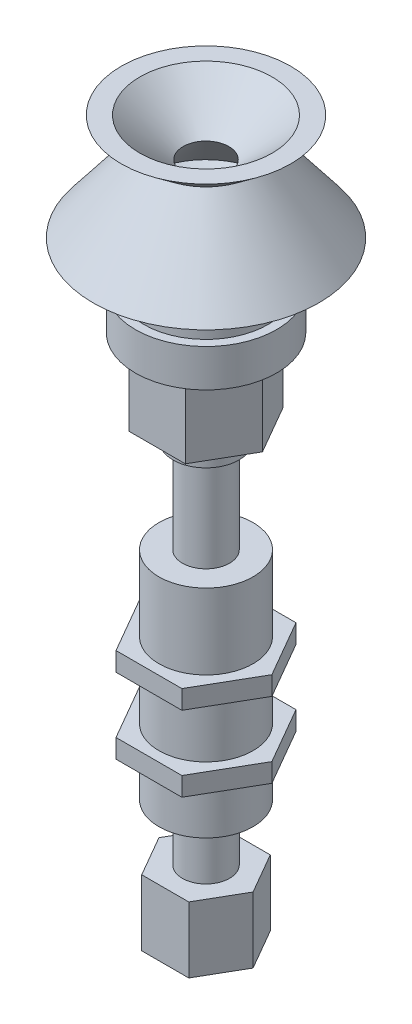
SolidWorks part; units mm, degrees
ref_plane "前视基准面" through (0, 0, 0) normal (0, 0, 1) x (1, 0, 0)
ref_plane "上视基准面" through (0, 0, 0) normal (0, 1, 0) x (1, 0, 0)
ref_plane "右视基准面" through (0, 0, 0) normal (1, 0, 0) x (0, 0, -1)
other "Configuration Table"
sketch "草图1" plane through (0, 0, 0) normal (0, 1, 0) x (1, 0, 0)
  line L1 (-2.5, -4.3301) -> (2.5, -4.3301)
  line L2 (2.5, -4.3301) -> (5, 0)
  line L3 (5, 0) -> (2.5, 4.3301)
  line L4 (2.5, 4.3301) -> (-2.5, 4.3301)
  line L5 (-2.5, 4.3301) -> (-5, 0)
  line L6 (-5, 0) -> (-2.5, -4.3301)
  circle A0 centre (0, 0) radius 4.3301 construction
  dimension "D1" = 5
extrude "凸台-拉伸1" add sketch "草图1" along normal blind 7
sketch "草图2" plane through (0, 7, 0) normal (0, 1, 0) x (1, 0, 0)
  circle A0 centre (0, 0) radius 2.5
  dimension "D1" = 5
extrude "凸台-拉伸2" add sketch "草图2" along normal blind 6
sketch "草图3" plane through (0, 13, 0) normal (0, 1, 0) x (1, 0, 0)
  circle A0 centre (0, 0) radius 5
  dimension "D1" = 10
extrude "凸台-拉伸3" add sketch "草图3" along normal blind 23
ref_plane "基准面1" through (0, 18, 0) normal (0, -1, 0) x (-1, 0, 0)
sketch "草图4" plane through (0, 18, 0) normal (0, -1, 0) x (-1, 0, 0)
  line L1 (3.5, -6.0622) -> (7, 0)
  line L2 (7, 0) -> (3.5, 6.0622)
  line L3 (3.5, 6.0622) -> (-3.5, 6.0622)
  line L4 (-3.5, 6.0622) -> (-7, 0)
  line L5 (-7, 0) -> (-3.5, -6.0622)
  line L6 (-3.5, -6.0622) -> (3.5, -6.0622)
  circle A0 centre (0, 0) radius 6.0622 construction
  dimension "D1" = 7
extrude "凸台-拉伸4" add sketch "草图4" against normal blind 2
ref_plane "基准面2" through (0, 28, 0) normal (0, 1, 0) x (1, 0, 0)
sketch "草图5" plane through (0, 28, 0) normal (0, 1, 0) x (1, 0, 0)
  line L6 (-3.5, -6.0622) -> (3.5, -6.0622)
  line L7 (3.5, -6.0622) -> (7, 0)
  line L8 (7, 0) -> (3.5, 6.0622)
  line L9 (3.5, 6.0622) -> (-3.5, 6.0622)
  line L10 (-3.5, 6.0622) -> (-7, 0)
  line L11 (-7, 0) -> (-3.5, -6.0622)
  line L12 (-3.5, -6.0622) -> (3.5, -6.0622)
  line L13 (3.5, -6.0622) -> (7, 0)
  line L14 (7, 0) -> (3.5, 6.0622)
  line L15 (3.5, 6.0622) -> (-3.5, 6.0622)
  line L16 (-3.5, 6.0622) -> (-7, 0)
  line L17 (-7, 0) -> (-3.5, -6.0622)
  dimension "D1" = 0
extrude "凸台-拉伸5" add sketch "草图5" against normal blind 2
sketch "草图6" plane through (0, 36, 0) normal (0, 1, 0) x (1, 0, 0)
  circle A0 centre (0, 0) radius 2.5
  dimension "D1" = 5
extrude "凸台-拉伸6" add sketch "草图6" along normal blind 10
sketch "草图7" plane through (0, 46, 0) normal (0, 1, 0) x (1, 0, 0)
  circle A0 centre (0, 0) radius 3.5
  dimension "D1" = 7
extrude "凸台-拉伸7" add sketch "草图7" along normal blind 2
sketch "草图8" plane through (0, 48, 0) normal (0, 1, 0) x (1, 0, 0)
  line L1 (-3, 5.1962) -> (-6, 0)
  line L2 (-6, 0) -> (-3, -5.1962)
  line L3 (-3, -5.1962) -> (3, -5.1962)
  line L4 (3, -5.1962) -> (6, 0)
  line L5 (6, 0) -> (3, 5.1962)
  line L6 (3, 5.1962) -> (-3, 5.1962)
  circle A0 centre (0, 0) radius 5.1962 construction
  dimension "D1" = 6
extrude "凸台-拉伸8" add sketch "草图8" along normal blind 8
sketch "草图9" plane through (0, 56, 0) normal (0, 1, 0) x (1, 0, 0)
  circle A0 centre (0, 0) radius 7.5
  dimension "D1" = 15
extrude "凸台-拉伸9" add sketch "草图9" along normal blind 4
sketch "草图10" plane through (0, 0, 0) normal (1, 0, 0) x (0, 0, -1)
  line L0 (0, 60) -> (6.578, 60)
  line L1 (7.5, 60) -> (-7.5, 60) construction
  line L2 (6.578, 60) -> (6.578, 61.5443)
  line L3 (6.578, 61.5443) -> (12, 64.7116)
  line L4 (12, 64.7116) -> (5.3989, 73.1993)
  line L5 (5.3989, 73.1993) -> (9, 76)
  line L6 (9, 76) -> (7.0268, 76)
  line L7 (0, 76) -> (0, 60) construction
  line L8 (-7.5, 56) -> (7.5, 56) construction
  line L9 (3.289, 60) -> (3.289, 64.3056)
  line L10 (3.289, 64.3056) -> (6.578, 67.2423)
  line L11 (6.578, 67.2423) -> (2.4262, 71.8923)
  line L12 (2.4262, 71.8923) -> (7.0268, 76)
  dimension "D1" = 9
  dimension "D2" = 20
  dimension "D3" = 12
revolve "旋转2" add sketch "草图10" angle 360 about L7
sketch "草图11" plane through (0, 76, 0) normal (0, 1, 0) x (1, 0, 0)
  point P0 (0, 0)
